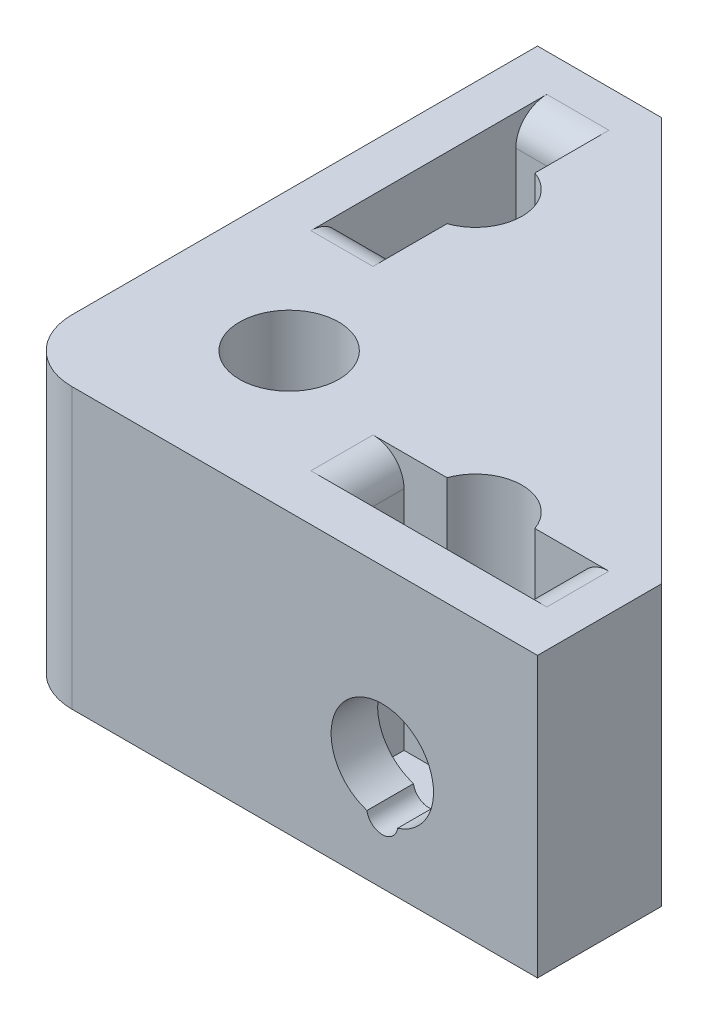
SolidWorks part; units mm, degrees
material "PET"
ref_plane "Front Plane" through (0, 0, 0) normal (0, 0, 1) x (1, 0, 0)
ref_plane "Top Plane" through (0, 0, 0) normal (0, 1, 0) x (1, 0, 0)
ref_plane "Right Plane" through (0, 0, 0) normal (1, 0, 0) x (0, 0, -1)
sketch "Sketch1" plane through (0, 0, 0) normal (0, 1, 0) x (1, 0, 0)
  line L2 (10.5, 10.5) -> (17, 4)
  line L3 (17, 4) -> (17, 0)
  line L4 (17, 0) -> (0, 0)
  line L5 (0, 0) -> (10.5, 10.5)
  dimension "D1" = 45
  dimension "D2" = 17
  dimension "D3" = 4
extrude "Boss-Extrude1" add sketch "Sketch1" along normal blind 9
sketch "Sketch2" plane through (0, 9, 0) normal (0, 1, 0) x (1, 0, 0)
  line L0 (0, 0) -> (35355.3391, 35355.3391) construction
  line L9 (0, 0) -> (17, 0) construction
  line L12 (9.2, 1.5) -> (9.2, 3.5)
  line L13 (14.8, 3.5) -> (9.2, 3.5)
  line L14 (14.8, 1.5) -> (14.8, 3.5)
  line L15 (14.8, 1.5) -> (9.2, 1.5)
  line L16 (0, 0) -> (17, 0) construction
  point P5 (12, 3.5)
  dimension "D1" = 45
  dimension "D2" = 12
  dimension "D6" = 1.5
  dimension "D8" = 2
  dimension "D9" = 5.6
extrude "Cut-Extrude1" cut sketch "Sketch2" against normal offset from surface (8.3 mm away) 0.7 up to face at (11.125, 0, -3.625)
sketch "Sketch4" plane through (0, 0, 0) normal (0, 0, 1) x (1, 0, 0)
  line L0 (12, 3.5) -> (14.8, 3.5) construction
  line L1 (12, 3.5) -> (12, 0.7) construction
  line L4 (14.8, 0.7) -> (14.8, 9)
  line L5 (14.8, 9) -> (9.2, 9)
  line L6 (9.2, 9) -> (9.2, 0.7)
  line L7 (9.2, 0.7) -> (14.8, 0.7)
  line L8 (14.8, 0.7) -> (14.8, 9) construction
  line L9 (14.8, 9) -> (9.2, 9) construction
  line L10 (9.2, 9) -> (9.2, 0.7) construction
  line L11 (9.2, 0.7) -> (14.8, 0.7) construction
  arc A0 (12.4945, 1.9258) -> (11.5055, 1.9258) centre (12, 3.5) ccw
  arc A1 (11.5055, 1.9258) -> (12.4945, 1.9258) centre (12, 2) ccw
  point P1 (12, 2.0001)
  point P10 (12, 3.5)
  dimension "D1" = 3.3
  dimension "D3" = 1
  dimension "D4" = 0.15
  dimension "D2" = 0
extrude "Cut-Extrude2" cut sketch "Sketch4" against normal through all
sketch "Sketch16" plane through (0, 9, 0) normal (0, 1, 0) x (1, 0, 0)
  line L0 (9.2, 1.5) -> (14.8, 1.5) construction
  line L1 (14.8, 3.5) -> (9.2, 3.5) construction
  circle A0 centre (12, 3) radius 1.5
  point P4 (12, 3.5)
  dimension "D1" = 3
extrude "Cut-Extrude5" cut sketch "Sketch16" against normal up to next
fillet "Fillet2" radius 1 2 edges at (9.2, 9, -2.5) (14.8, 9, -2.5)
sketch "Sketch6" plane through (0, 9, 0) normal (0, 1, 0) x (1, 0, 0)
  line L0 (12, 1.5) -> (12, 6.8) construction
  line L1 (9.2, 1.5) -> (14.8, 1.5) construction
  line L2 (12, 1.5) -> (12, -3.2) construction
  line L3 (0, 0) -> (17, 0) construction
  line L5 (10.5, 10.5) -> (0, 0) construction
  circle A0 centre (4.5, 4.5) radius 1.6
  dimension "D3" = 3.2
  dimension "D1" = 3.2
  dimension "D2" = 10
  dimension "D4" = 4.5
extrude "Cut-Extrude3" cut sketch "Sketch6" against normal through all
sketch "Sketch9" plane through (0, 0, 0) normal (0, -1, 0) x (1, 0, 0)
  line L0 (3.3686, -3.3686) -> (0, 0) construction
  line L1 (7.5115, -5.3069) -> (6.7045, -2.2955)
  line L2 (6.7045, -2.2955) -> (3.6931, -1.4885)
  line L3 (3.6931, -1.4885) -> (1.4885, -3.6931)
  line L4 (1.4885, -3.6931) -> (2.2955, -6.7045)
  line L5 (2.2955, -6.7045) -> (5.3069, -7.5115)
  line L6 (5.3069, -7.5115) -> (7.5115, -5.3069)
  circle A0 centre (4.5, -4.5) radius 2.7 construction
  dimension "D1" = 5.4
extrude "Cut-Extrude4" cut sketch "Sketch9" against normal blind 3
fillet "Fillet3" radius 1 4 edges at (3.1419, 0, -2.0397) (5.1988, 0, -1.892) (7.108, 0, -3.8012) (6.9603, 0, -5.8581)
mirror "Mirror1" about plane through (0, 9, 0) normal (0.7071, 0, 0.7071) of bodies 106 103
fillet "Fillet1" radius 2 1 edges at (0, 4.5, 0)
